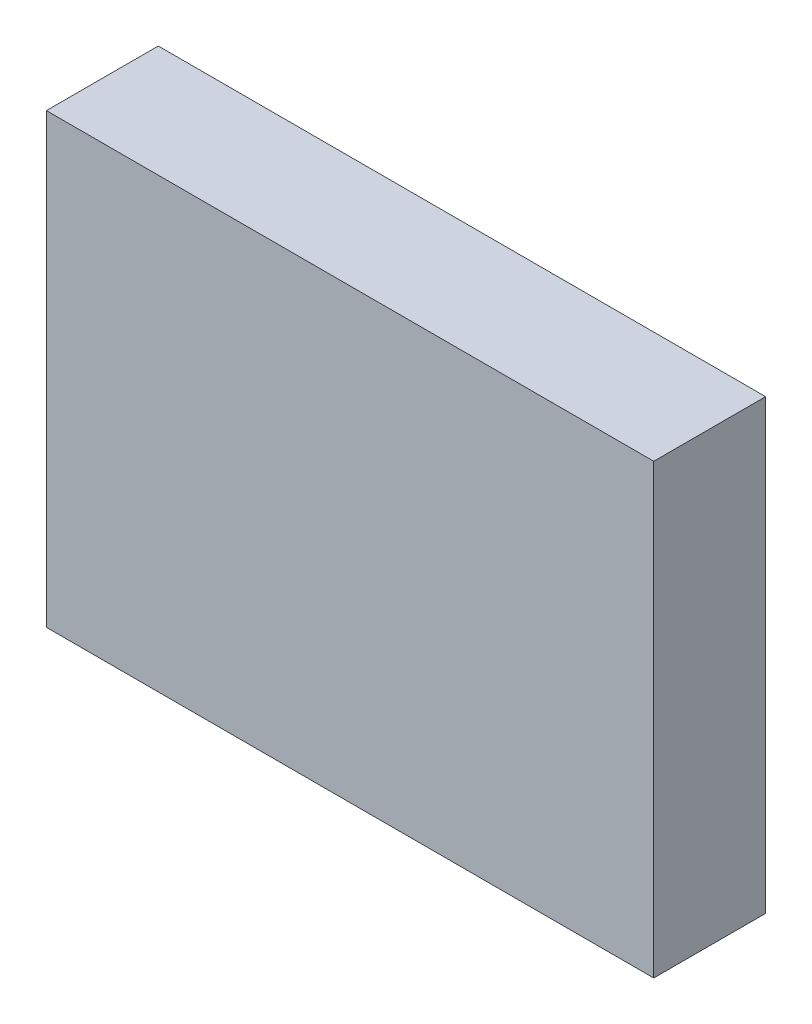
SolidWorks part; units mm, degrees
ref_plane "前视基准面" through (0, 0, 0) normal (0, 0, 1) x (1, 0, 0)
ref_plane "上视基准面" through (0, 0, 0) normal (0, 1, 0) x (1, 0, 0)
ref_plane "右视基准面" through (0, 0, 0) normal (1, 0, 0) x (0, 0, -1)
sketch "草图1" plane through (0, 0, 0) normal (0, 0, 1) x (1, 0, 0)
  line L0 (1.9, -1.4) -> (1.9, 1.4)
  line L1 (1.9, 1.4) -> (-1.9, 1.4)
  line L2 (-1.9, 1.4) -> (-1.9, -1.4)
  line L3 (-1.9, -1.4) -> (1.9, -1.4)
extrude "Component_Outline" add sketch "草图1" along normal blind 0.7 separate body
sketch3d "3D草图1"
  line L0 (0, 0, 0) -> (1, 0, 0)
  line L1 (0, 0, 0) -> (0, 1, 0)
  line L2 (0, 0, 0) -> (0, 0, 1)
  point P0 (0, 0, 0)
